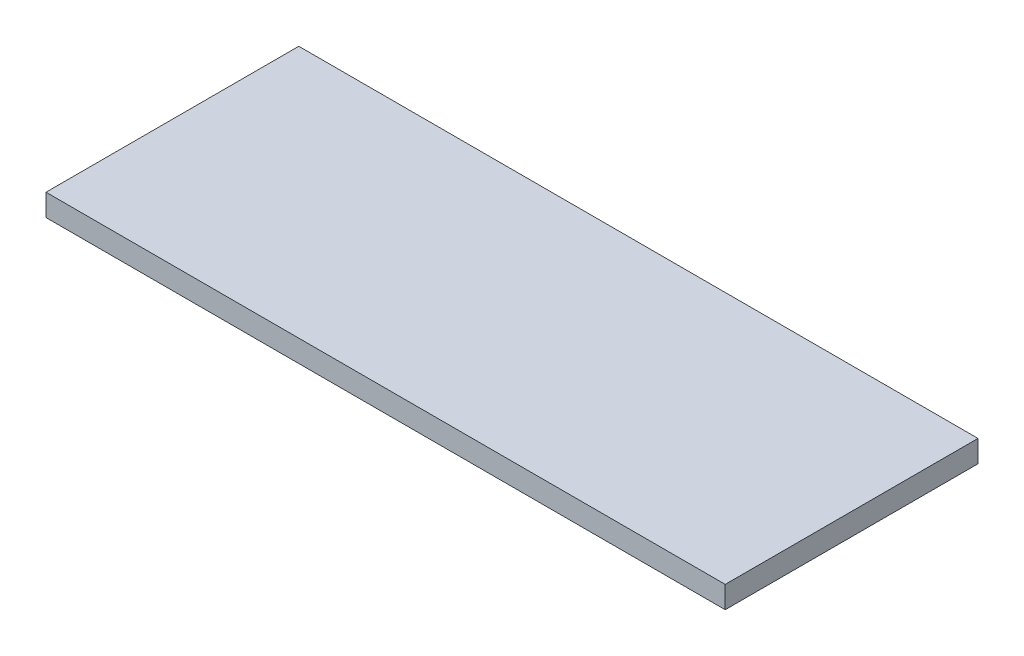
SolidWorks part; units mm, degrees
ref_plane "Front Plane" through (0, 0, 0) normal (0, 0, 1) x (1, 0, 0)
ref_plane "Top Plane" through (0, 0, 0) normal (0, 1, 0) x (1, 0, 0)
ref_plane "Right Plane" through (0, 0, 0) normal (1, 0, 0) x (0, 0, -1)
sketch "Sketch1" plane through (0, 0, 0) normal (0, 1, 0) x (1, 0, 0)
  line L1 (0, 0) -> (309, 0)
  line L2 (0, 0) -> (0, 115)
  line L3 (0, 115) -> (309, 115)
  line L4 (309, 0) -> (309, 115)
  dimension "D1" = 309
  dimension "D2" = 115
extrude "Boss-Extrude1" add sketch "Sketch1" along normal blind 10
